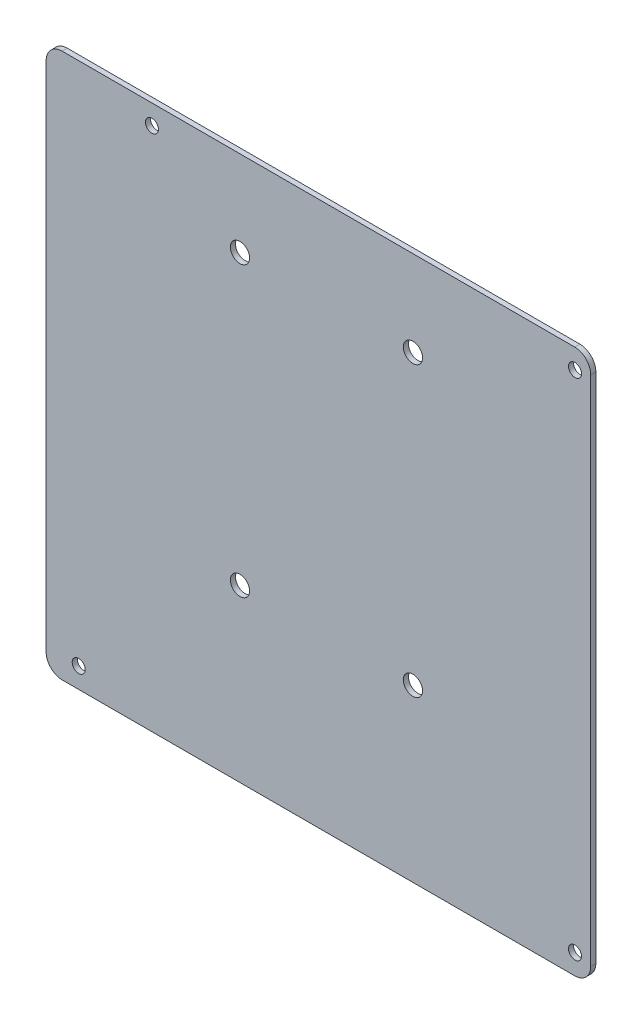
SolidWorks part; units mm, degrees
ref_plane "Plan de face" through (0, 0, 0) normal (0, 0, 1) x (1, 0, 0)
ref_plane "Plan de dessus" through (0, 0, 0) normal (0, 1, 0) x (1, 0, 0)
ref_plane "Plan de droite" through (0, 0, 0) normal (1, 0, 0) x (0, 0, -1)
sketch "Esquisse1" plane through (0, 0, 0) normal (0, 0, 1) x (1, 0, 0)
  line L0 (-15.0797, -111.0472) -> (-15.0797, 48.9528)
  line L1 (-10.0797, 53.9528) -> (149.9203, 53.9528)
  line L2 (154.9203, 48.9528) -> (154.9203, -111.0472)
  line L3 (149.9203, -116.0472) -> (-10.0797, -116.0472)
  arc A0 (154.9203, -111.0472) -> (149.9203, -116.0472) centre (149.9203, -111.0472) cw
  arc A1 (149.9203, 53.9528) -> (154.9203, 48.9528) centre (149.9203, 48.9528) cw
  arc A2 (-15.0797, 48.9528) -> (-10.0797, 53.9528) centre (-10.0797, 48.9528) cw
  arc A3 (-15.0797, -111.0472) -> (-10.0797, -116.0472) centre (-10.0797, -111.0472) ccw
  circle A4 centre (-4.9197, -109.6972) radius 2.032
  circle A5 centre (17.9403, 47.7828) radius 2.032
  circle A6 centre (150.0203, 47.7828) radius 2.032
  circle A7 centre (150.0203, -109.6972) radius 2.032
  circle A8 centre (45.4203, -62.7472) radius 3
  circle A9 centre (45.4203, 27.2528) radius 3
  circle A10 centre (99.4203, 27.2528) radius 3
  circle A11 centre (99.4203, -62.7472) radius 3
  point P10 (154.9203, 53.9528)
  point P13 (-15.0797, 53.9528)
  dimension "D2" = 5
  dimension "D1" = 170
extrude "Boss.-Extru.1" add sketch "Esquisse1" along normal blind 1.6
